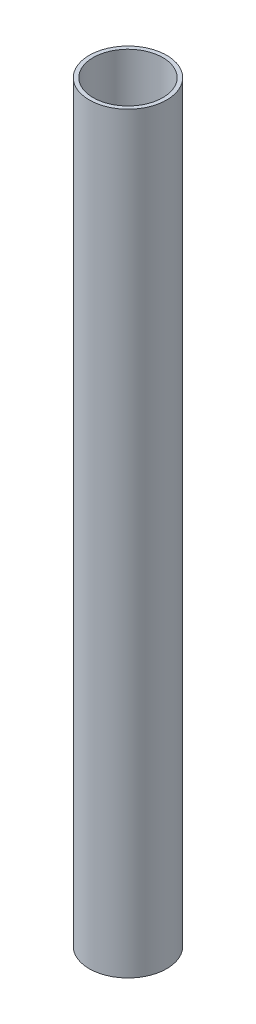
SolidWorks part; units mm, degrees
ref_plane "Спереди" through (0, 0, 0) normal (0, 0, 1) x (1, 0, 0)
ref_plane "Сверху" through (0, 0, 0) normal (0, 1, 0) x (1, 0, 0)
ref_plane "Справа" through (0, 0, 0) normal (1, 0, 0) x (0, 0, -1)
sketch "Эскиз1" plane through (0, 0, 0) normal (0, 1, 0) x (1, 0, 0)
  circle A0 centre (0, 0) radius 11.1
  circle A1 centre (0, 0) radius 12.35
  dimension "D1" = 22.2
  dimension "D2" = 24.7
extrude "Вытянуть1" add sketch "Эскиз1" along normal blind 240
